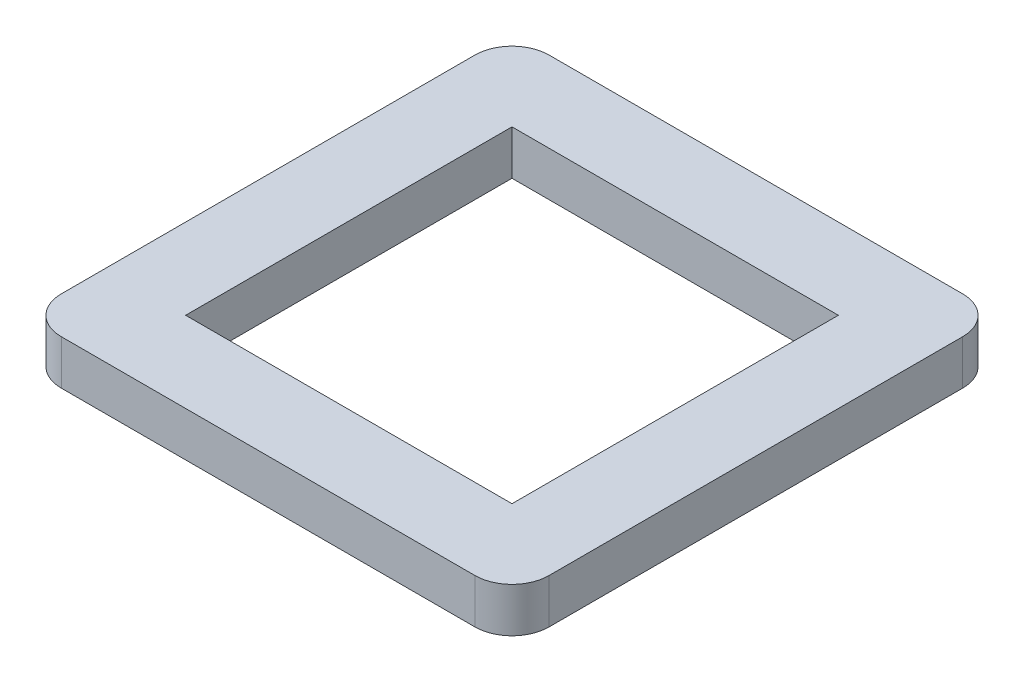
SolidWorks part; units mm, degrees
ref_plane "Front Plane" through (0, 0, 0) normal (0, 0, 1) x (1, 0, 0)
ref_plane "Top Plane" through (0, 0, 0) normal (0, 1, 0) x (1, 0, 0)
ref_plane "Right Plane" through (0, 0, 0) normal (1, 0, 0) x (0, 0, -1)
other "Default"
sketch "Sketch1" plane through (0, 0, 0) normal (0, 1, 0) x (1, 0, 0)
  line L1 (-69.5, -69.5) -> (69.5, -69.5)
  line L2 (-69.5, -69.5) -> (-69.5, 69.5)
  line L3 (-69.5, 69.5) -> (69.5, 69.5)
  line L4 (69.5, -69.5) -> (69.5, 69.5)
  line L5 (-69.5, -69.5) -> (69.5, 69.5) construction
  line L6 (-69.5, 69.5) -> (69.5, -69.5) construction
  point P0 (0, 0)
  dimension "Size" = 139
extrude "Boss-Extrude1" add sketch "Sketch1" along normal mid plane 12.7
fillet "Fillet1" radius 10.56 4 edges at (69.5, 0, 69.5) (69.5, 0, -69.5) (-69.5, 0, -69.5) (-69.5, 0, 69.5)
sketch "Sketch2" plane through (0, 6.35, 0) normal (0, 1, 0) x (1, 0, 0)
  line L1 (-46.5, -46.5) -> (46.5, -46.5)
  line L2 (-46.5, -46.5) -> (-46.5, 46.5)
  line L3 (-46.5, 46.5) -> (46.5, 46.5)
  line L4 (46.5, -46.5) -> (46.5, 46.5)
  line L5 (-46.5, -46.5) -> (46.5, 46.5) construction
  line L6 (-46.5, 46.5) -> (46.5, -46.5) construction
  point P0 (0, 0)
  dimension "SlotSize" = 93
extrude "SlotCut" cut sketch "Sketch2" against normal through all
sketch "Sketch3" plane through (0, 6.35, 0) normal (0, 1, 0) x (1, 0, 0)
  line L1 (-41.19, -41.19) -> (41.19, -41.19) construction
  line L2 (-41.19, -41.19) -> (-41.19, 41.19) construction
  line L3 (-41.19, 41.19) -> (41.19, 41.19) construction
  line L4 (41.19, -41.19) -> (41.19, 41.19) construction
  line L5 (-41.19, -41.19) -> (41.19, 41.19) construction
  line L6 (-41.19, 41.19) -> (41.19, -41.19) construction
  circle A0 centre (0, 0) radius 44.3
  circle A1 centre (-41.19, 41.19) radius 2.25
  circle A2 centre (41.19, 41.19) radius 2.25
  circle A3 centre (41.19, -41.19) radius 2.25
  circle A4 centre (-41.19, -41.19) radius 2.25
  dimension "HoleSize" = 4.5
  dimension "MiddleDiameter" = 88.6
  dimension "HoleDistance" = 82.38
extrude "HoleCut" [suppressed] cut sketch "Sketch3" against normal through all
